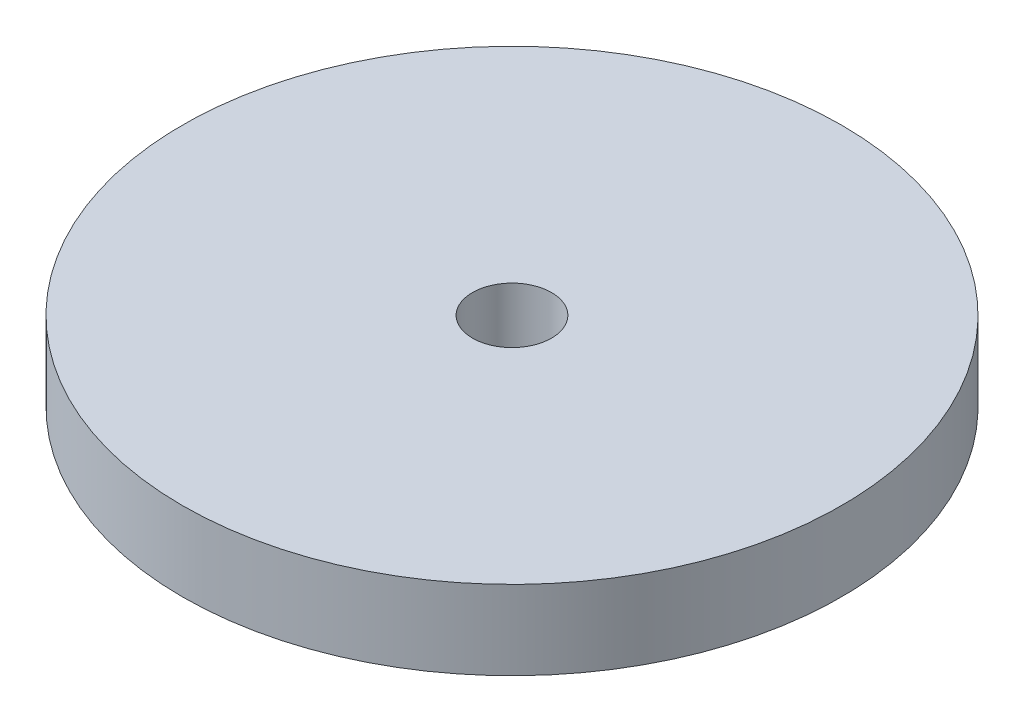
SolidWorks part; units mm, degrees
ref_plane "Piano frontale" through (0, 0, 0) normal (0, 0, 1) x (1, 0, 0)
ref_plane "Piano superiore" through (0, 0, 0) normal (0, 1, 0) x (1, 0, 0)
ref_plane "Piano destro" through (0, 0, 0) normal (1, 0, 0) x (0, 0, -1)
sketch "Schizzo1" plane through (0, 0, 0) normal (0, 1, 0) x (1, 0, 0)
  circle A0 centre (0, 0) radius 12.5
  circle A1 centre (0, 0) radius 1.5
  dimension "D1" = 25
  dimension "D2" = 3
extrude "Estrusione-Estrusione1" add sketch "Schizzo1" along normal blind 3
